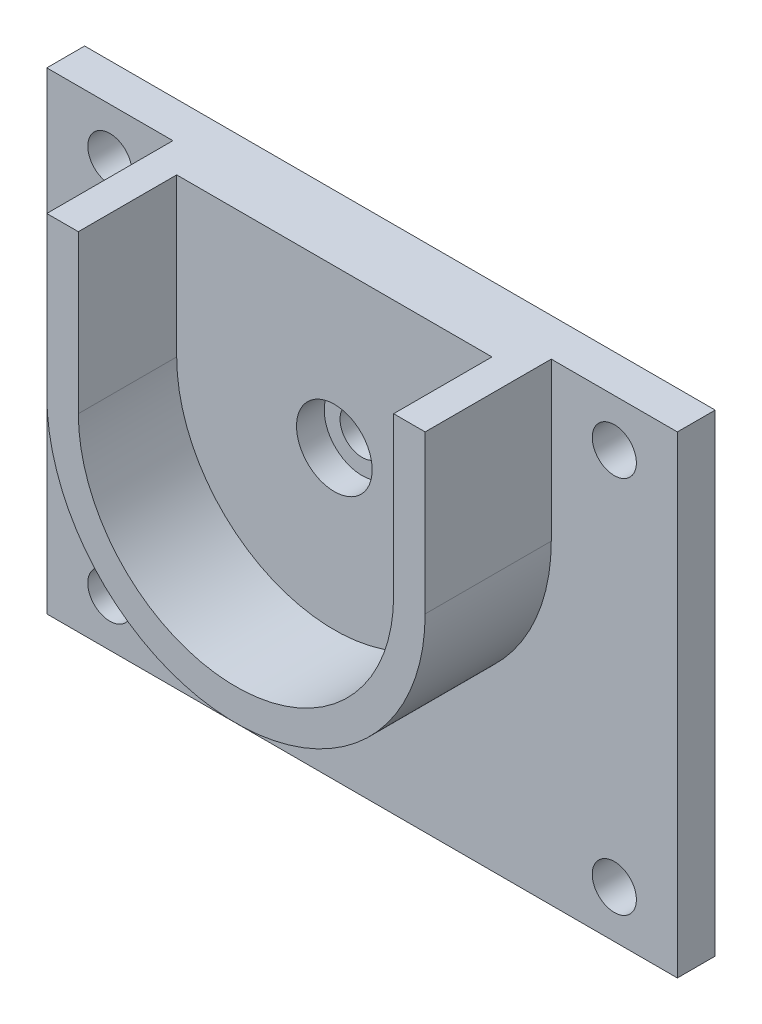
SolidWorks part; units mm, degrees
ref_plane "Piano frontale" through (0, 0, 0) normal (0, 0, 1) x (1, 0, 0)
ref_plane "Piano superiore" through (0, 0, 0) normal (0, 1, 0) x (1, 0, 0)
ref_plane "Piano destro" through (0, 0, 0) normal (1, 0, 0) x (0, 0, -1)
sketch "Schizzo1" plane through (0, 0, 0) normal (0, 0, 1) x (1, 0, 0)
  line L1 (-25, 12.5) -> (25, 12.5)
  line L2 (-25, 12.5) -> (-25, -25)
  line L3 (-25, -25) -> (25, -25)
  line L4 (25, 12.5) -> (25, -25)
  line L5 (-25, 12.5) -> (25, -25) construction
  line L6 (-25, -25) -> (25, 12.5) construction
  line L7 (-20, 8.75) -> (20, 8.75) construction
  line L8 (-20, 8.75) -> (-20, -21.25) construction
  line L9 (-20, -21.25) -> (20, -21.25) construction
  line L10 (20, 8.75) -> (20, -21.25) construction
  circle A0 centre (0, 0) radius 12.5
  arc A1 (-8.2916, 12.5) -> (8.2916, 12.5) centre (0, 0) ccw
  circle A2 centre (0, 0) radius 1.75
  circle A3 centre (-20, 8.75) radius 1.75
  circle A4 centre (-20, -21.25) radius 1.75
  circle A5 centre (20, -21.25) radius 1.75
  circle A6 centre (20, 8.75) radius 1.75
  point P4 (0, -6.25)
  point P9 (0, 12.5)
  dimension "D1" = 25
  dimension "D2" = 30
  dimension "D4" = 25
  dimension "D5" = 3.5
  dimension "D8" = 3.5
  dimension "D3" = 50
  dimension "D6" = 40
  dimension "D7" = 3.75
extrude "Estrusione-Estrusione1" add sketch "Schizzo1" along normal blind 3 contours A1 L1 L2 L3 L4 A6 A5 A4 A3 | L1 A1 A0 | A0 A2
sketch "Schizzo2" plane through (0, 0, 3) normal (0, 0, 1) x (1, 0, 0)
  line L1 (15, 0) -> (15, 12.5)
  line L2 (-25, 12.5) -> (25, 12.5) construction
  line L4 (-15, 0) -> (-15, 12.5)
  line L5 (-12.5, 0) -> (-12.5, 12.5)
  line L6 (-12.5, 12.5) -> (-15, 12.5)
  line L7 (12.5, 0) -> (12.5, 12.5)
  line L8 (12.5, 12.5) -> (15, 12.5)
  arc A0 (-12.5, 0) -> (12.5, 0) centre (0, 0) ccw
  arc A1 (-15, 0) -> (15, 0) centre (0, 0) ccw
  dimension "D1" = 25
  dimension "D2" = 30
extrude "Estrusione-Estrusione2" add sketch "Schizzo2" along normal blind 10
sketch "Schizzo3" plane through (0, 0, 3) normal (0, 0, 1) x (1, 0, 0)
  line L3 (12.5, 0) -> (12.5, 12.5)
  line L4 (12.5, 12.5) -> (-12.5, 12.5)
  line L5 (-12.5, 12.5) -> (-12.5, 0)
  line L6 (12.5, 0) -> (12.5, 12.5)
  line L7 (12.5, 12.5) -> (-12.5, 12.5)
  line L8 (-12.5, 12.5) -> (-12.5, 0)
  circle A0 centre (0, 0) radius 3
  arc A1 (-12.5, 0) -> (12.5, 0) centre (0, 0) ccw
  arc A2 (-12.5, 0) -> (12.5, 0) centre (0, 0) ccw
  dimension "D2" = 6
  dimension "D1" = 0
extrude "Estrusione-Estrusione3" add sketch "Schizzo3" along normal blind 2.2
